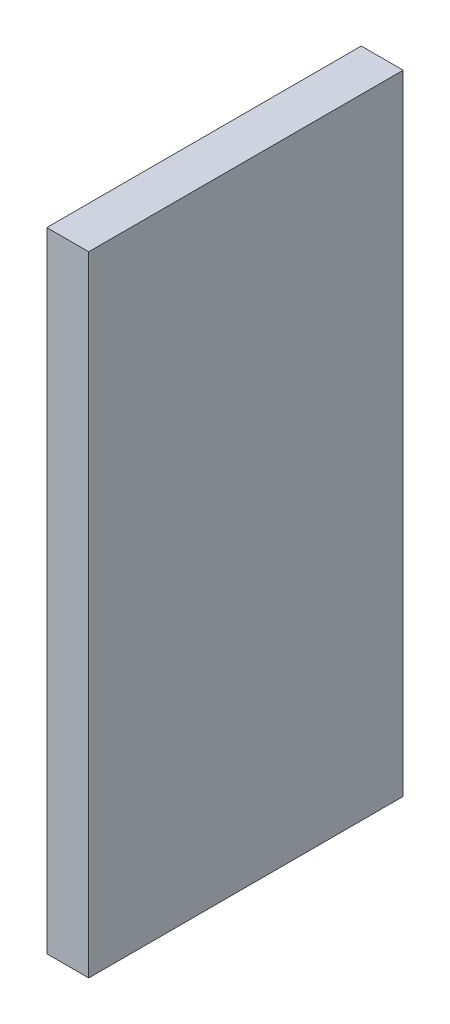
SolidWorks part; units mm, degrees
ref_plane "Front Plane" through (0, 0, 0) normal (0, 0, 1) x (1, 0, 0)
ref_plane "Top Plane" through (0, 0, 0) normal (0, 1, 0) x (1, 0, 0)
ref_plane "Right Plane" through (0, 0, 0) normal (1, 0, 0) x (0, 0, -1)
sketch "Sketch1" plane through (0, 0, 0) normal (0, 1, 0) x (1, 0, 0)
  line L1 (0, 0) -> (4, 0)
  line L2 (0, 0) -> (0, 30)
  line L3 (0, 30) -> (4, 30)
  line L4 (4, 0) -> (4, 30)
  dimension "D1" = 30
  dimension "D2" = 4
extrude "Boss-Extrude1" add sketch "Sketch1" along normal blind 60 contours L4 L3 L2 L1
